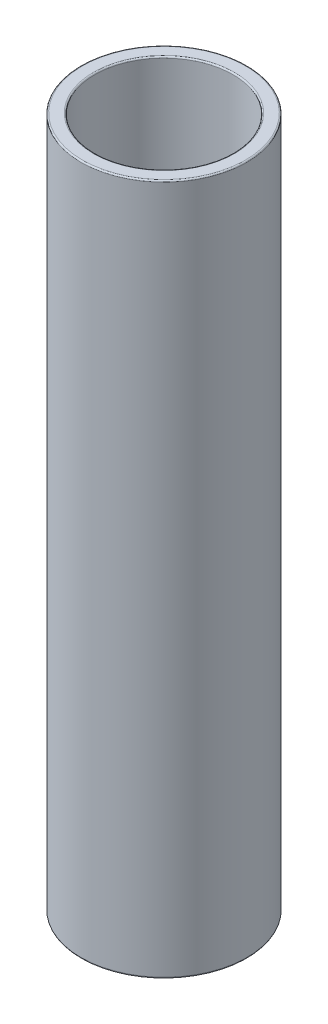
SolidWorks part; units mm, degrees
material "Aluminum Bronze"
ref_plane "Front Plane" through (0, 0, 0) normal (0, 0, 1) x (1, 0, 0)
ref_plane "Top Plane" through (0, 0, 0) normal (0, 1, 0) x (1, 0, 0)
ref_plane "Right Plane" through (0, 0, 0) normal (1, 0, 0) x (0, 0, -1)
sketch "Sketch1" plane through (0, 0, 0) normal (0, 1, 0) x (1, 0, 0)
  circle A0 centre (0, 0) radius 2.5
  circle A1 centre (0, 0) radius 3
  dimension "D1" = 5
  dimension "D2" = 6
extrude "Boss-Extrude1" add sketch "Sketch1" along normal mid plane 25
fillet "Fillet1" radius 0.05 4 edges at (0, -12.5, 2.5) (0, -12.5, 3) (0, 12.5, 2.5) (0, 12.5, 3)
